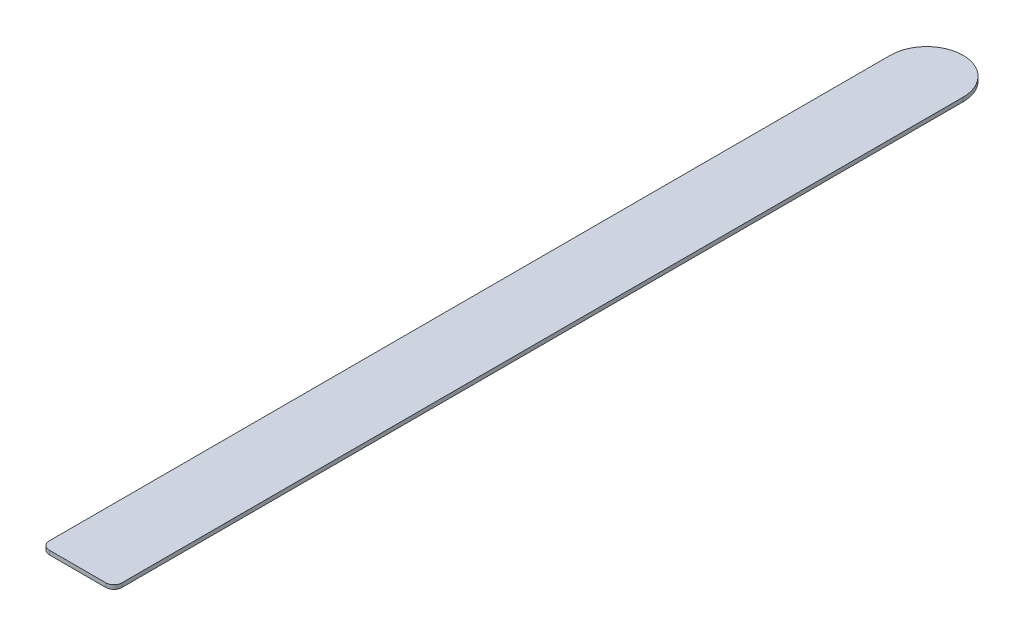
SolidWorks part; units mm, degrees
ref_plane "Front Plane" through (0, 0, 0) normal (0, 0, 1) x (1, 0, 0)
ref_plane "Top Plane" through (0, 0, 0) normal (0, 1, 0) x (1, 0, 0)
ref_plane "Right Plane" through (0, 0, 0) normal (1, 0, 0) x (0, 0, -1)
sketch "Sketch1" plane through (0, 0, 0) normal (0, 1, 0) x (1, 0, 0)
  line L0 (-44.7, 0) -> (-44.7, -1044.7)
  line L1 (-44.7, -1044.7) -> (44.7, -1044.7)
  line L2 (44.7, -1044.7) -> (44.7, 0)
  circle A0 centre (0, 0) radius 44.7
  dimension "D1" = 89.4
  dimension "D2" = 1044.7
extrude "Boss-Extrude1" add sketch "Sketch1" along normal blind 5 contours A0 L0 L1 L2 | A0
fillet "Fillet1" radius 10 2 edges at (-44.7, 2.5, 1044.7) (44.7, 2.5, 1044.7)
